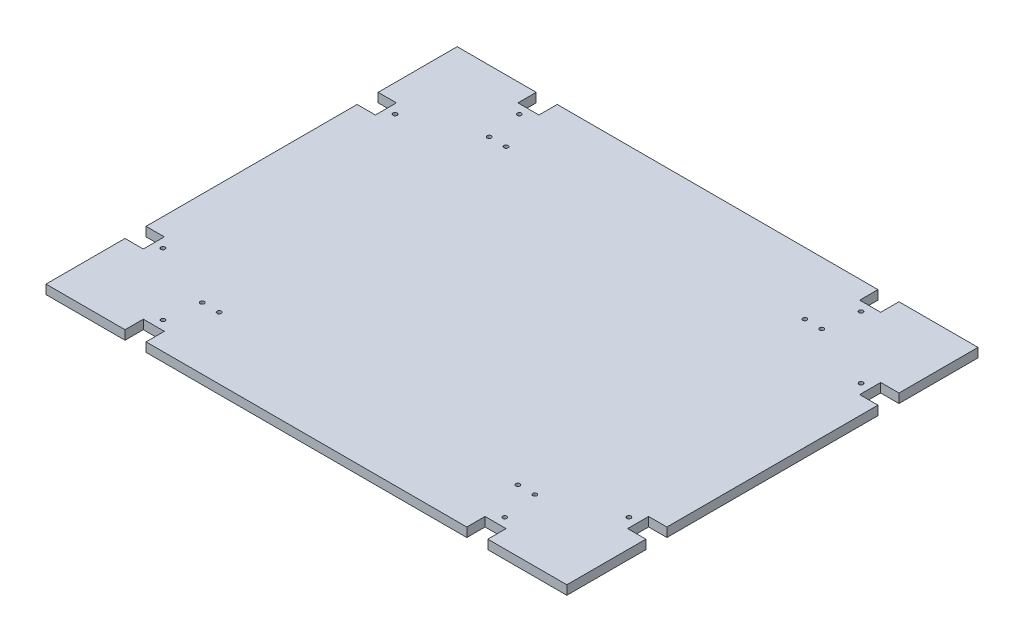
SolidWorks part; units mm, degrees
material "Pino"
ref_plane "Piano frontale" through (0, 0, 0) normal (0, 0, 1) x (1, 0, 0)
ref_plane "Piano superiore" through (0, 0, 0) normal (0, 1, 0) x (1, 0, 0)
ref_plane "Piano destro" through (0, 0, 0) normal (1, 0, 0) x (0, 0, -1)
sketch "Schizzo1" plane through (0, 0, 0) normal (0, 1, 0) x (1, 0, 0)
  line L1 (0, 0) -> (-570, 0)
  line L2 (0, 0) -> (0, 450)
  line L3 (0, 450) -> (-570, 450)
  line L4 (-570, 0) -> (-570, 450)
  dimension "D1" = 570
  dimension "D2" = 450
extrude "Estrusione-Estrusione1" add sketch "Schizzo1" along normal blind 10
sketch "Schizzo2" plane through (0, 0, 0) normal (0, -1, 0) x (1, 0, 0)
  line L0 (-570, 0) -> (0, 0) construction
  line L1 (-483.5, 0) -> (-460.5, 0)
  line L3 (-483.5, 0) -> (-483.5, -20)
  line L5 (-483.5, -20) -> (-460.5, -20)
  line L6 (-460.5, 0) -> (-460.5, -20)
  line L7 (-483.5, 0) -> (-460.5, -20) construction
  line L8 (-483.5, -20) -> (-460.5, 0) construction
  line L9 (0, 0) -> (0, -450) construction
  line L10 (-109.5, 0) -> (-86.5, 0)
  line L11 (-109.5, 0) -> (-109.5, -20)
  line L12 (-109.5, -20) -> (-86.5, -20)
  line L13 (-86.5, 0) -> (-86.5, -20)
  line L14 (-109.5, 0) -> (-86.5, -20) construction
  line L15 (-109.5, -20) -> (-86.5, 0) construction
  line L16 (0, -86.5) -> (-20, -86.5)
  line L17 (0, -86.5) -> (0, -109.5)
  line L18 (0, -109.5) -> (-20, -109.5)
  line L19 (-20, -86.5) -> (-20, -109.5)
  line L20 (0, -86.5) -> (-20, -109.5) construction
  line L21 (0, -109.5) -> (-20, -86.5) construction
  line L22 (0, -450) -> (-570, -450) construction
  line L23 (0, -340.5) -> (-20, -340.5)
  line L24 (0, -340.5) -> (0, -363.5)
  line L25 (0, -363.5) -> (-20, -363.5)
  line L26 (-20, -340.5) -> (-20, -363.5)
  line L27 (0, -340.5) -> (-20, -363.5) construction
  line L28 (0, -363.5) -> (-20, -340.5) construction
  line L29 (-86.5, -450) -> (-109.5, -450)
  line L30 (-86.5, -450) -> (-86.5, -430)
  line L31 (-86.5, -430) -> (-109.5, -430)
  line L32 (-109.5, -450) -> (-109.5, -430)
  line L33 (-86.5, -450) -> (-109.5, -430) construction
  line L34 (-86.5, -430) -> (-109.5, -450) construction
  line L35 (-570, -450) -> (-570, 0) construction
  line L36 (-460.5, -450) -> (-483.5, -450)
  line L37 (-460.5, -450) -> (-460.5, -430)
  line L38 (-460.5, -430) -> (-483.5, -430)
  line L39 (-483.5, -450) -> (-483.5, -430)
  line L40 (-460.5, -450) -> (-483.5, -430) construction
  line L41 (-460.5, -430) -> (-483.5, -450) construction
  line L42 (-570, -363.5) -> (-550, -363.5)
  line L43 (-570, -363.5) -> (-570, -340.5)
  line L44 (-570, -340.5) -> (-550, -340.5)
  line L45 (-550, -363.5) -> (-550, -340.5)
  line L46 (-570, -363.5) -> (-550, -340.5) construction
  line L47 (-570, -340.5) -> (-550, -363.5) construction
  line L48 (-560, -98) -> (-10, -98) construction
  line L49 (-570, -109.5) -> (-550, -109.5)
  line L50 (-570, -109.5) -> (-570, -86.5)
  line L51 (-570, -86.5) -> (-550, -86.5)
  line L52 (-550, -109.5) -> (-550, -86.5)
  line L53 (-570, -109.5) -> (-550, -86.5) construction
  line L54 (-570, -86.5) -> (-550, -109.5) construction
  line L55 (-472, -10) -> (-472, -440) construction
  line L56 (-98, -440) -> (-98, -10) construction
  line L57 (-560, -352) -> (-10, -352) construction
  circle A2 centre (-467, -68) radius 2.25
  circle A3 centre (-448.5, -68) radius 2.25
  circle A6 centre (-121.5, -68) radius 2.25
  circle A7 centre (-103, -68) radius 2.25
  circle A8 centre (-467, -382) radius 2.25
  circle A9 centre (-448.5, -382) radius 2.25
  circle A14 centre (-121.5, -382) radius 2.25
  circle A15 centre (-103, -382) radius 2.25
  circle A16 centre (-472, -420) radius 2.25
  circle A17 centre (-540, -352) radius 2.25
  circle A18 centre (-540, -98) radius 2.25
  circle A19 centre (-472, -30) radius 2.25
  circle A20 centre (-98, -30) radius 2.25
  circle A21 centre (-30, -98) radius 2.25
  circle A22 centre (-30, -352) radius 2.25
  circle A23 centre (-98, -420) radius 2.25
  point P4 (-472, -10)
  point P17 (-98, -10)
  point P34 (-10, -98)
  point P41 (-10, -352)
  point P52 (-98, -440)
  point P59 (-472, -440)
  point P64 (-560, -352)
  point P71 (-560, -98)
  dimension "D1" = 4.5
  dimension "D3" = 98
  dimension "D5" = 98
  dimension "D2" = 98
  dimension "D4" = 98
  dimension "D6" = 23
  dimension "D7" = 20
extrude "Taglio-Estrusione1" cut sketch "Schizzo2" against normal blind 10
